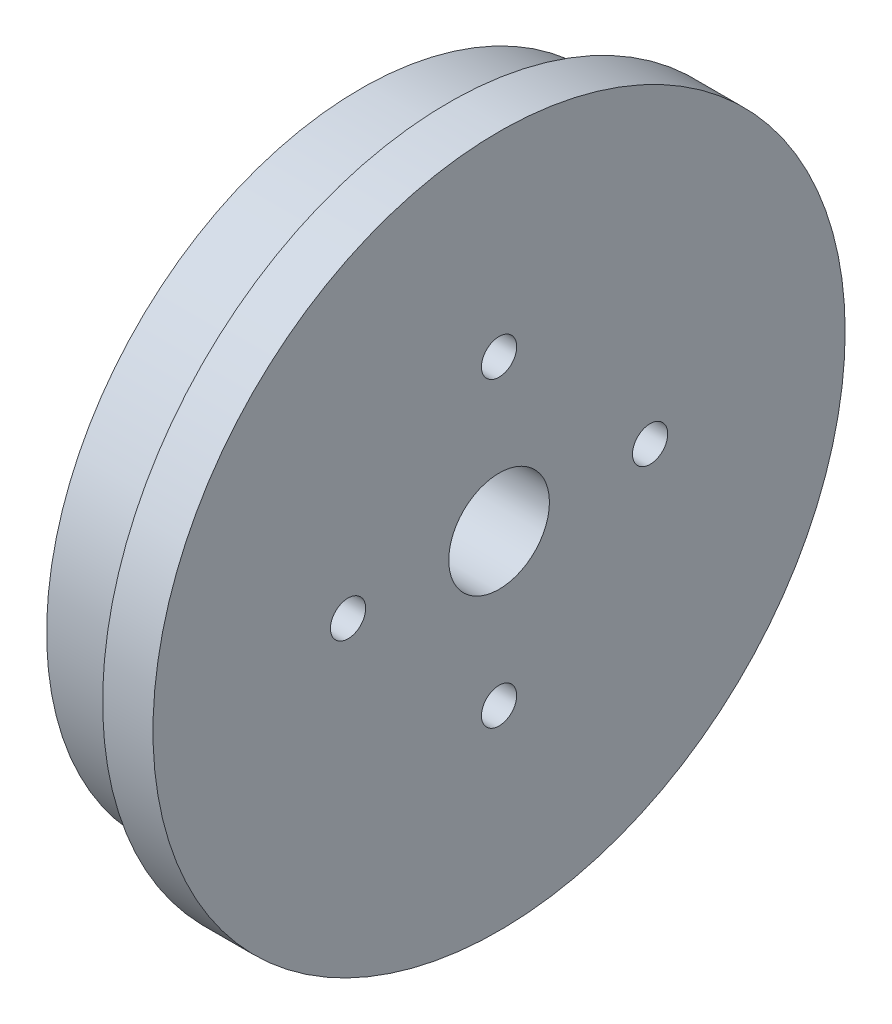
SolidWorks part; units mm, degrees
ref_plane "Front Plane" through (0, 0, 0) normal (0, 0, 1) x (1, 0, 0)
ref_plane "Top Plane" through (0, 0, 0) normal (0, 1, 0) x (1, 0, 0)
ref_plane "Right Plane" through (0, 0, 0) normal (1, 0, 0) x (0, 0, -1)
sketch "Sketch1" plane through (0, 0, 0) normal (1, 0, 0) x (0, 0, -1)
  circle A0 centre (0, 0) radius 24.95
  dimension "D1" = 49.9
extrude "Hub" add sketch "Sketch1" along normal blind 7
sketch "Sketch2" plane through (7, 0, 0) normal (1, 0, 0) x (0, 0, -1)
  circle A0 centre (0, 0) radius 27.5
  dimension "D1" = 55
extrude "Shoulder" add sketch "Sketch2" along normal blind 4
sketch "Sketch3" plane through (11, 0, 0) normal (1, 0, 0) x (0, 0, -1)
  circle A0 centre (0, 0) radius 4
  dimension "D1" = 8
extrude "Cut-Extrude1" cut sketch "Sketch3" against normal through all
sketch "Sketch5" plane through (11, 0, 0) normal (1, 0, 0) x (0, 0, -1)
  circle A0 centre (-12, 0) radius 1.4
  circle A1 centre (0, 12) radius 1.4
  circle A2 centre (12, 0) radius 1.4
  circle A3 centre (0, -12) radius 1.4
  point P12 (0, 0)
  dimension "D1" = 2.8
  dimension "D2" = 12
  dimension "D3" = 4
extrude "Cut-Extrude3" cut sketch "Sketch5" against normal blind 8
sketch "Sketch6" plane through (0, 0, 0) normal (-1, 0, 0) x (0, 0, 1)
  circle A0 centre (0, 20) radius 3
  circle A1 centre (18.1865, 10.5) radius 3
  circle A2 centre (19.0526, -10) radius 3
  circle A3 centre (1.7321, -21) radius 3
  circle A4 centre (-16.4545, -11.5) radius 3
  circle A5 centre (-17.3205, 9) radius 3
  point P15 (0.866, -0.5)
  dimension "D1" = 6
  dimension "D2" = 20
  dimension "D3" = 6
extrude "Cut-Extrude4" cut sketch "Sketch6" against normal blind 6
